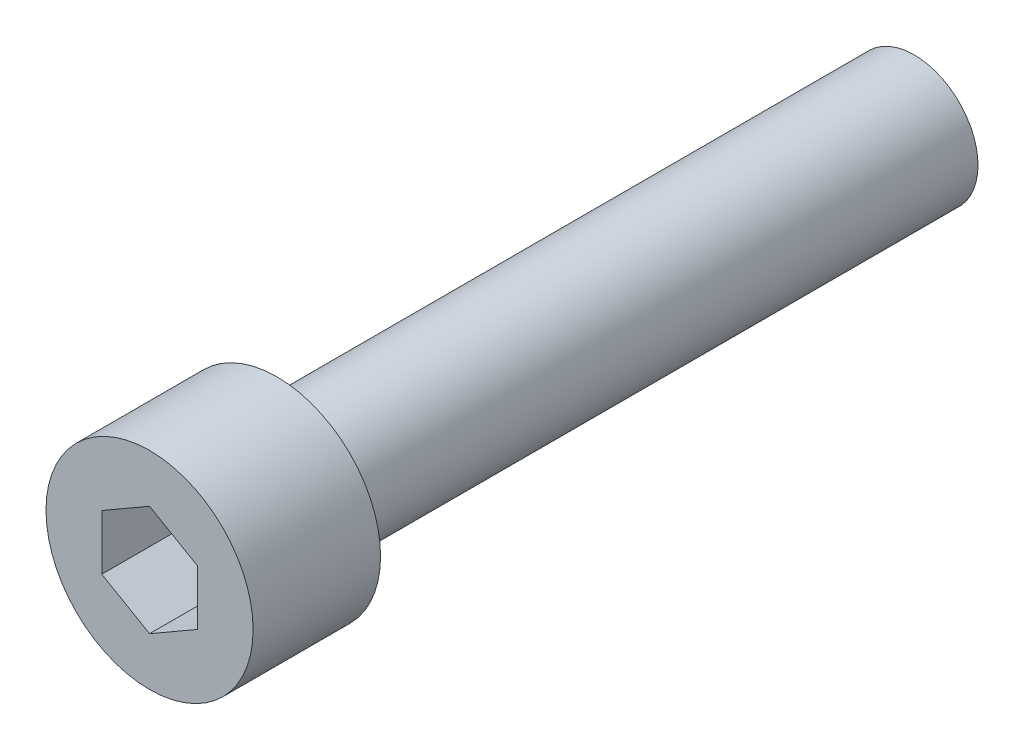
SolidWorks part; units mm, degrees
ref_plane "Płaszczyzna przednia" through (0, 0, 0) normal (0, 0, 1) x (1, 0, 0)
ref_plane "Płaszczyzna górna" through (0, 0, 0) normal (0, 1, 0) x (1, 0, 0)
ref_plane "Płaszczyzna prawa" through (0, 0, 0) normal (1, 0, 0) x (0, 0, -1)
sketch "Szkic1" plane through (0, 0, 0) normal (1, 0, 0) x (0, 0, -1)
  line L0 (0, 0) -> (30.4213, 0) construction
  line L1 (0, 0) -> (0, 6.5)
  line L2 (0, 6.5) -> (8, 6.5)
  line L3 (8, 6.5) -> (8, 4)
  line L4 (8, 4) -> (48, 4)
  line L5 (48, 4) -> (48, 0)
  line L6 (48, 0) -> (0, 0)
  dimension "D1" = 13
  dimension "D2" = 8
  dimension "D3" = 8
  dimension "D4" = 40
revolve "Obrót1" add sketch "Szkic1" angle 360 about L0
sketch "Szkic2" plane through (0, 0, 0) normal (0, 0, 1) x (1, 0, 0)
  line L1 (-3, -1.7321) -> (0, -3.4641)
  line L2 (0, -3.4641) -> (3, -1.7321)
  line L3 (3, -1.7321) -> (3, 1.7321)
  line L4 (3, 1.7321) -> (0, 3.4641)
  line L5 (0, 3.4641) -> (-3, 1.7321)
  line L6 (-3, 1.7321) -> (-3, -1.7321)
  circle A0 centre (0, 0) radius 3 construction
  dimension "D1" = 6
extrude "Wytnij-wyciągnięcie1" cut sketch "Szkic2" against normal blind 6
